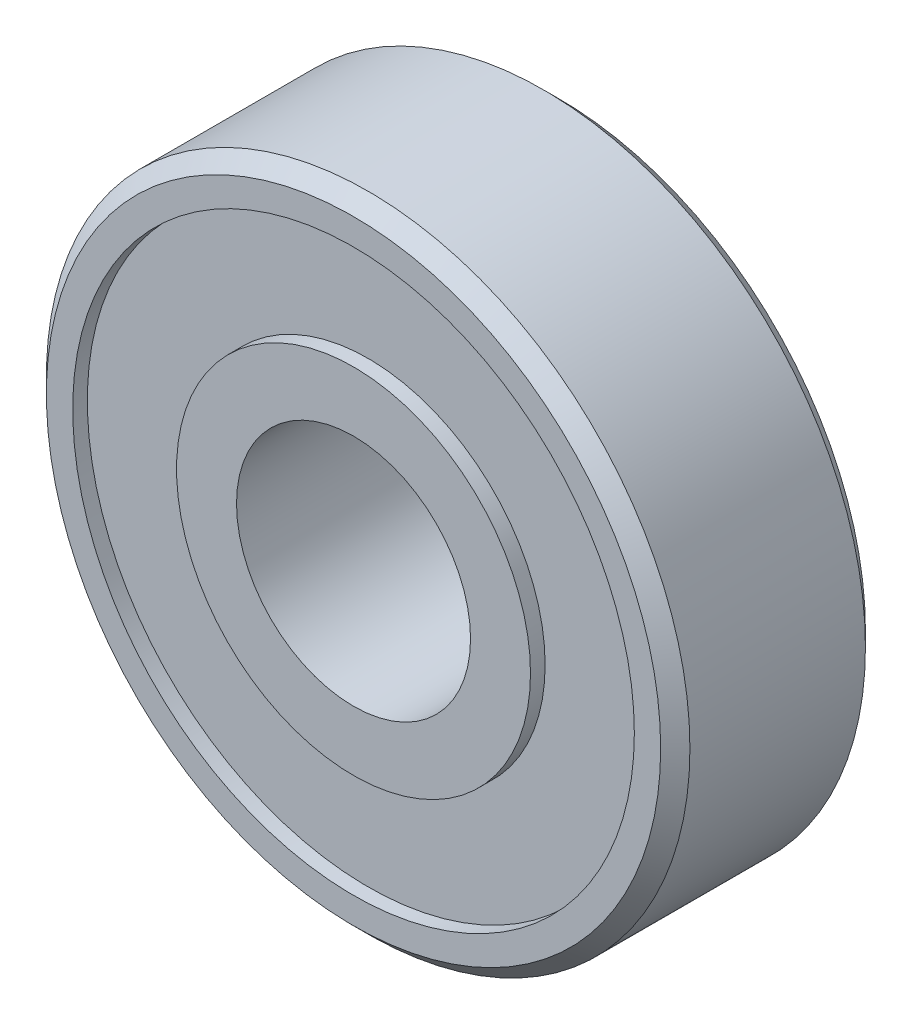
SolidWorks part; units mm, degrees
ref_plane "정면" through (0, 0, 0) normal (0, 0, 1) x (1, 0, 0)
ref_plane "윗면" through (0, 0, 0) normal (0, 1, 0) x (1, 0, 0)
ref_plane "우측면" through (0, 0, 0) normal (1, 0, 0) x (0, 0, -1)
sketch "스케치1" plane through (0, 0, 0) normal (0, 0, 1) x (1, 0, 0)
  circle A0 centre (0, 0) radius 11
  circle A1 centre (0, 0) radius 4
  dimension "D1" = 22
  dimension "D2" = 8
extrude "보스-돌출1" add sketch "스케치1" along normal mid plane 7
chamfer "모따기1" distance 0.5 angle 45 2 edges at (11, 0, -3.5) (11, 0, 3.5)
sketch "스케치2" plane through (0, 0, 3.5) normal (0, 0, 1) x (1, 0, 0)
  circle A0 centre (0, 0) radius 9.6
  circle A1 centre (0, 0) radius 10.5
  circle A2 centre (0, 0) radius 10.5
  circle A3 centre (0, 0) radius 6.05
  dimension "D2" = 19.2
  dimension "D3" = 12.1
  dimension "D1" = 0
extrude "컷-돌출1" cut sketch "스케치2" against normal blind 0.5 contours A0 A3
mirror "대칭 복사1" about plane through (0, 0, 0) normal (0, 0, 1) of "컷-돌출1"
